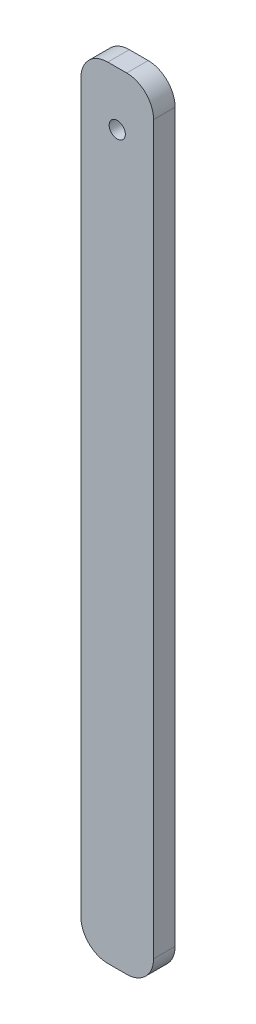
SolidWorks part; units mm, degrees
material "Beech"
ref_plane "Front" through (0, 0, 0) normal (0, 0, 1) x (1, 0, 0)
ref_plane "Top" through (0, 0, 0) normal (0, 1, 0) x (1, 0, 0)
ref_plane "Right" through (0, 0, 0) normal (1, 0, 0) x (0, 0, -1)
sketch "Sketch1" plane through (0, 0, 0) normal (0, 0, 1) x (1, 0, 0)
  line L1 (-3.5, -145) -> (3.5, -145)
  line L2 (-13.5, -135) -> (-13.5, 135)
  line L3 (-3.5, 145) -> (3.5, 145)
  line L4 (13.5, -135) -> (13.5, 135)
  line L5 (-13.5, -145) -> (13.5, 145) construction
  line L6 (-13.5, 145) -> (13.5, -145) construction
  circle A0 centre (0, 125) radius 3
  arc A1 (-3.5, -145) -> (-13.5, -135) centre (-3.5, -135) cw
  arc A2 (3.5, -145) -> (13.5, -135) centre (3.5, -135) ccw
  arc A3 (-13.5, 135) -> (-3.5, 145) centre (-3.5, 135) cw
  arc A4 (3.5, 145) -> (13.5, 135) centre (3.5, 135) cw
  point P0 (0, 0)
  dimension "D1" = 6
  dimension "D5" = 10
  dimension "D2" = 27
  dimension "D3" = 290
  dimension "D4" = 20
extrude "Boss-Extrude1" add sketch "Sketch1" along normal blind 8 contours A4 L3 A3 L2 A1 L1 A2 L4 A0
